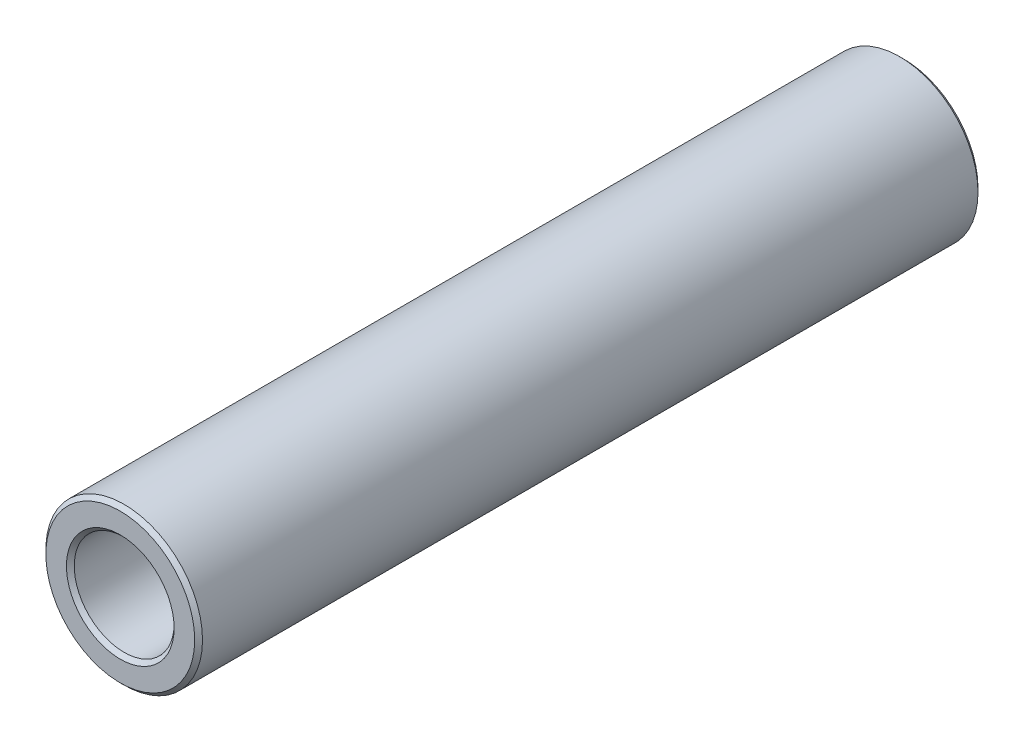
SolidWorks part; units mm, degrees
material "Aluminium"
ref_plane "Front Plane" through (0, 0, 0) normal (0, 0, 1) x (1, 0, 0)
ref_plane "Top Plane" through (0, 0, 0) normal (0, 1, 0) x (1, 0, 0)
ref_plane "Right Plane" through (0, 0, 0) normal (1, 0, 0) x (0, 0, -1)
sketch "Sketch1" plane through (0, 0, 0) normal (0, 0, 1) x (1, 0, 0)
  circle A0 centre (0, 0) radius 2.55
  circle A1 centre (0, 0) radius 4
  dimension "D1" = 5.1
  dimension "D2" = 8
extrude "Boss-Extrude1" add sketch "Sketch1" along normal blind 40
chamfer "Chamfer1" distance 0.2 angle 45 4 edges at (4, 0, 0) (2.55, 0, 0) (2.55, 0, 40) (4, 0, 40)
